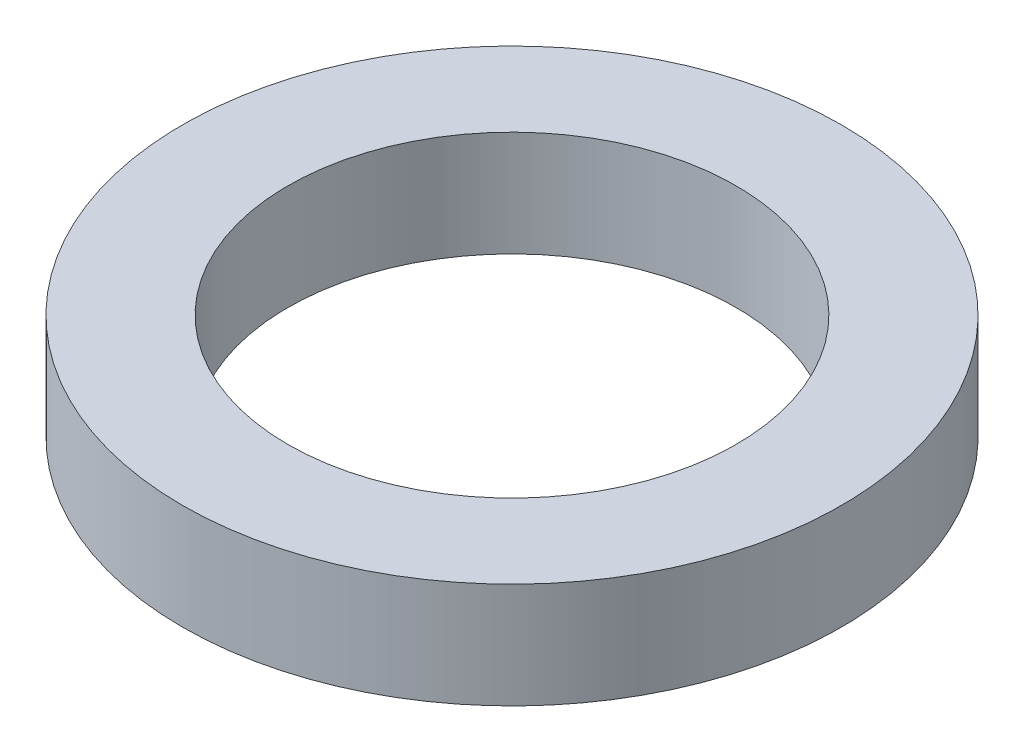
SolidWorks part; units mm, degrees
ref_plane "前视基准面" through (0, 0, 0) normal (0, 0, 1) x (1, 0, 0)
ref_plane "上视基准面" through (0, 0, 0) normal (0, 1, 0) x (1, 0, 0)
ref_plane "右视基准面" through (0, 0, 0) normal (1, 0, 0) x (0, 0, -1)
sketch "草图1" plane through (0, 0, 0) normal (0, 1, 0) x (1, 0, 0)
  circle A0 centre (0, 0) radius 1.7
  circle A1 centre (0, 0) radius 2.5
  dimension "D1" = 0.8
extrude "凸台-拉伸1" add sketch "草图1" along normal blind 0.8
